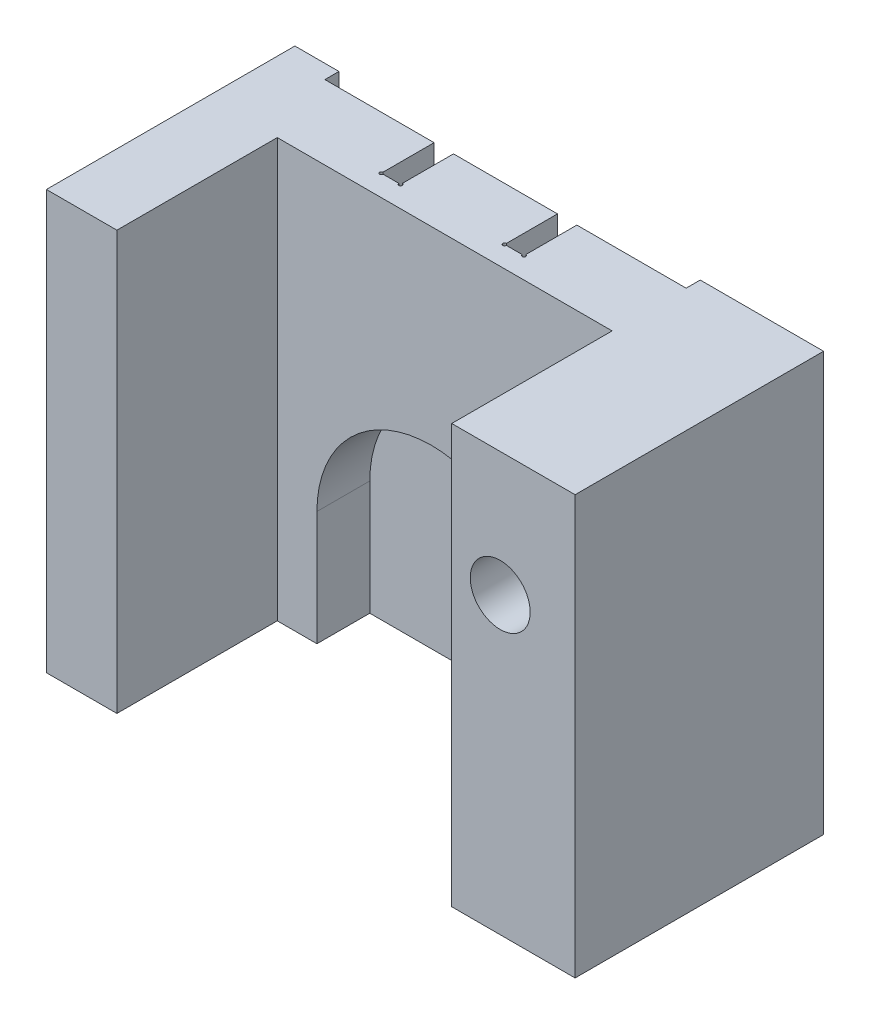
SolidWorks part; units mm, degrees
ref_plane "前视基准面" through (0, 0, 0) normal (0, 0, 1) x (1, 0, 0)
ref_plane "上视基准面" through (0, 0, 0) normal (0, 1, 0) x (1, 0, 0)
ref_plane "右视基准面" through (0, 0, 0) normal (1, 0, 0) x (0, 0, -1)
sketch "草图1" plane through (0, 0, 0) normal (0, 0, 1) x (1, 0, 0)
  line L1 (-7.5503, 16.7364) -> (22.4497, 16.7364)
  line L2 (-7.5503, 16.7364) -> (-7.5503, -11.2636)
  line L3 (-7.5503, -11.2636) -> (22.4497, -11.2636)
  line L4 (22.4497, 16.7364) -> (22.4497, -11.2636)
  dimension "D1" = 30
  dimension "D2" = 28
extrude "凸台-拉伸1" add sketch "草图1" along normal blind 10
sketch "草图2" plane through (0, 0, 0) normal (0, 0, -1) x (-1, 0, 0)
  line L0 (-22.4497, 16.7364) -> (7.5503, 16.7364) construction
  line L1 (7.5503, 16.7364) -> (7.5503, -11.2636) construction
  line L3 (5.0503, 16.7364) -> (-15.4497, 16.7364)
  line L4 (5.0503, 16.7364) -> (5.0503, 3.7364)
  line L5 (2.0503, 0.7364) -> (-12.4497, 0.7364)
  line L6 (-15.4497, 16.7364) -> (-15.4497, 3.7364)
  arc A0 (2.0503, 0.7364) -> (5.0503, 3.7364) centre (2.0503, 3.7364) ccw
  arc A1 (-12.4497, 0.7364) -> (-15.4497, 3.7364) centre (-12.4497, 3.7364) cw
  point P0 (5.0503, 16.7364)
  point P11 (5.0503, 0.7364)
  dimension "D4" = 3
  dimension "D1" = 2.5
  dimension "D2" = 20.5
  dimension "D3" = 16
extrude "切除-拉伸2" cut sketch "草图2" against normal blind 0.8
sketch "草图3" plane through (0, 0, 0.8) normal (0, 0, -1) x (-1, 0, 0)
  line L0 (5.0503, 16.7364) -> (-15.4497, 16.7364) construction
  line L2 (-15.1997, 16.7364) -> (4.8003, 16.7364)
  line L3 (-15.1997, 16.7364) -> (-15.1997, 3.7364)
  line L4 (-12.1997, 0.7364) -> (1.8003, 0.7364)
  line L5 (4.8003, 16.7364) -> (4.8003, 3.7364)
  arc A0 (1.8003, 0.7364) -> (4.8003, 3.7364) centre (1.8003, 3.7364) ccw
  arc A1 (-12.1997, 0.7364) -> (-15.1997, 3.7364) centre (-12.1997, 3.7364) cw
  point P0 (-5.1997, 16.7364)
  point P9 (4.8003, 0.7364)
  point P12 (1.8003, 13.7364)
  point P14 (-12.1997, 13.7364)
  dimension "D4" = 3
  dimension "D1" = 20
  dimension "D2" = 10
  dimension "D3" = 16
  dimension "D5" = 3
  dimension "D6" = 3
  dimension "D7" = 3
  dimension "D8" = 3
hole_wizard "M1.4x0.3 螺纹孔2" positions "草图9" profile "草图7" tap size "M1.4x0.3" standard "ANSI Metric"
sketch "草图9" plane through (0, 0, 0.8) normal (0, 0, -1) x (-1, 0, 0)
  line L1 (-15.1997, 16.7364) -> (4.8003, 16.7364) construction
  point P0 (-12.1997, 8.7364)
  point P3 (1.8003, 8.7364)
  dimension "D1" = 8
  dimension "D2" = 8
sketch "草图7" plane through (12.1997, 8.7364, 0.8) normal (1, 0, 0) x (0, 1, 0)
  line L0 (0, 0) -> (0, 4.0305)
  line L1 (0, 4.0305) -> (0.55, 3.7)
  line L2 (0.55, 3.7) -> (0.55, 0)
  line L5 (0.55, 0) -> (0, 0)
  line L10 (0, 4.0305) -> (-0.55, 3.7) construction
  line L11 (0, -6.35) -> (0, 107.95) construction
  dimension "螺纹孔钻头直径" = 1.1
  dimension "螺纹孔钻头深度" = 3.7
  dimension "导头角度" = 118
cosmetic thread "孔螺蚊线7" parameters "D1"=3.5, "D2"=1.4
cosmetic thread "孔螺蚊线8" parameters "D1"=3.5, "D2"=1.4
sketch "草图10" plane through (0, 16.7364, 0) normal (0, 1, 0) x (1, 0, 0)
  line L0 (22.4497, -0.8) -> (-7.5503, -0.8)
  line L1 (22.4497, -10) -> (22.4497, 0) construction
  line L2 (-7.5503, -10) -> (-7.5503, 0) construction
  line L3 (22.4497, 0) -> (15.4497, 0) construction
  line L5 (9.2497, -0.8) -> (8.1497, -0.8)
  line L6 (9.2497, -0.8) -> (9.2497, -3.7)
  line L7 (9.1495, -3.8) -> (8.2497, -3.8)
  line L8 (8.1497, -0.8) -> (8.1497, -3.7)
  line L9 (1.1497, -0.8) -> (2.2497, -0.8)
  line L10 (1.1497, -0.8) -> (1.1497, -3.7043)
  line L11 (1.2454, -3.8) -> (2.1461, -3.8)
  line L12 (2.2497, -0.8) -> (2.2497, -3.6964)
  arc A0 (9.1495, -3.8) -> (9.2497, -3.7) centre (9.2495, -3.8) ccw
  arc A1 (8.1497, -3.7) -> (8.2497, -3.8) centre (8.1497, -3.8) ccw
  arc A2 (2.1461, -3.8) -> (2.2497, -3.6964) centre (2.2497, -3.8) ccw
  arc A3 (1.1497, -3.7043) -> (1.2454, -3.8) centre (1.1497, -3.8) ccw
  point P8 (5.1997, -0.8)
  point P9 (9.2497, -0.8)
  point P10 (1.1497, -0.8)
  dimension "D9" = 0.1
  dimension "D10" = 0.1
  dimension "D1" = 0.8
  dimension "D2" = 4.05
  dimension "D3" = 4.05
  dimension "D4" = 3
  dimension "D5" = 1.1
  dimension "D6" = 1.1
  dimension "D7" = 3
  dimension "D8" = 12.75
extrude "切除-拉伸3" cut sketch "草图10" against normal blind 4 contours L8 A1 L7 A0 L6 L5 | L10 A3 L11 A2 L12 L9
sketch "草图11" plane through (0, 0, 0) normal (0, 0, -1) x (-1, 0, 0)
  line L0 (-12.1997, 0.7364) -> (1.8003, 0.7364) construction
  line L1 (-7.5497, -2.0636) -> (-2.8497, -2.0636)
  line L2 (-7.7997, 0.7364) -> (-2.5997, 0.7364)
  line L3 (-7.7997, 0.7364) -> (-7.7997, -1.8136)
  line L5 (-2.5997, 0.7364) -> (-2.5997, -1.8136)
  arc A0 (-2.8497, -2.0636) -> (-2.5997, -1.8136) centre (-2.5997, -2.0636) ccw
  arc A1 (-7.7997, -1.8136) -> (-7.5497, -2.0636) centre (-7.7997, -2.0636) ccw
  point P0 (-5.1997, 0.7364)
  dimension "D4" = 2.8
  dimension "D5" = 0.5
  dimension "D6" = 0.5
  dimension "D1" = 5.2
  dimension "D2" = 2.6
  dimension "D3" = 2.8
  dimension "D7" = 2.8
  dimension "D8" = 2.8
  dimension "D9" = 4.7
extrude "切除-拉伸4" cut sketch "草图11" against normal blind 0.5
sketch "草图12" plane through (0, 0, 0) normal (0, 0, -1) x (-1, 0, 0)
  line L0 (-22.4497, -11.2636) -> (-22.4497, 16.7364) construction
  line L1 (7.5503, -11.2636) -> (-22.4497, -11.2636)
  line L2 (7.5503, -11.2636) -> (7.5503, -7.0136)
  line L3 (7.5503, -7.0136) -> (-22.4497, -7.0136)
  line L4 (-22.4497, -11.2636) -> (-22.4497, -7.0136)
  dimension "D1" = 4.25
extrude "切除-拉伸5" cut sketch "草图12" against normal blind 10
sketch "草图13" plane through (0, 0, 0) normal (0, 0, -1) x (-1, 0, 0)
  line L1 (-7.5497, -2.0636) -> (-2.8497, -2.0636) construction
  line L3 (-7.5497, -2.0636) -> (-2.8497, -2.0636) construction
  circle A0 centre (-18.1997, 9.6864) radius 1.7
  point P0 (-18.1997, 9.6864)
  point P6 (-5.1997, -2.0636)
  dimension "D3" = 3.4
  dimension "D1" = 13
  dimension "D2" = 11.75
extrude "切除-拉伸6" cut sketch "草图13" against normal blind 10
sketch "草图14" plane through (0, 0, 10) normal (0, 0, 1) x (1, 0, 0)
  line L0 (-7.5503, -7.0136) -> (22.4497, -7.0136) construction
  line L1 (-7.5503, 16.7364) -> (15.4497, 16.7364)
  line L2 (-7.5503, 16.7364) -> (-7.5503, -7.0136)
  line L3 (-7.5503, -7.0136) -> (15.4497, -7.0136)
  line L4 (15.4497, 16.7364) -> (15.4497, -7.0136)
  line L5 (22.4497, -7.0136) -> (22.4497, 16.7364) construction
  dimension "D1" = 7
extrude "切除-拉伸7" cut sketch "草图14" against normal blind 5
sketch "草图16" plane through (0, 0, 5) normal (0, 0, 1) x (1, 0, 0)
  line L2 (-7.5503, -7.0136) -> (15.4497, -7.0136) construction
  line L3 (-7.5503, 16.7364) -> (-7.5503, -7.0136) construction
  line L5 (-1.3003, -7.0136) -> (11.6997, -7.0136)
  line L7 (-1.3003, -7.0136) -> (-1.3003, -0.5136)
  line L9 (11.6997, -7.0136) -> (11.6997, -0.5136)
  arc A0 (11.6997, -0.5136) -> (-1.3003, -0.5136) centre (5.1997, -0.5136) ccw
  point P0 (5.1997, -7.0136)
  dimension "D4" = 6.5
  dimension "D5" = 6.5
  dimension "D1" = 12.75
  dimension "D2" = 13
  dimension "D3" = 6.5
sketch "草图17" plane through (0, 0, 0.5) normal (0, 0, -1) x (-1, 0, 0)
  line L0 (-2.5997, 0.7364) -> (-7.7997, 0.7364) construction
  line L3 (1.3003, -7.0136) -> (-11.6997, -7.0136) construction
  point P0 (-5.1997, 0.7364)
  point P1 (-5.1997, -0.5136)
  dimension "D1" = 6.5
extrude "切除-拉伸9" cut sketch "草图16" against normal blind 3
sketch "草图20" plane through (0, 0, 10) normal (0, 0, 1) x (1, 0, 0)
  line L1 (15.4497, 16.7364) -> (22.4497, 16.7364)
  line L2 (15.4497, 16.7364) -> (15.4497, -7.0136)
  line L3 (15.4497, -7.0136) -> (22.4497, -7.0136)
  line L4 (22.4497, 16.7364) -> (22.4497, -7.0136)
  circle A0 centre (18.1997, 9.6864) radius 1.7
  dimension "D1" = 3.4
extrude "凸台-拉伸3" add sketch "草图20" along normal blind 4.1
sketch "草图21" plane through (0, 0, 0.8) normal (0, 0, -1) x (-1, 0, 0)
  point P0 (-5.1997, 16.7364)
sketch "草图22" plane through (0, 16.7364, 0) normal (0, 1, 0) x (1, 0, 0)
  line L0 (5.1997, -0.8) -> (5.1997, -5)
  line L1 (15.4497, -5) -> (-7.5503, -5) construction
sketch "草图23" plane through (0, 0, 5) normal (0, 0, 1) x (1, 0, 0)
  line L0 (-7.5503, -7.0136) -> (-1.3003, -7.0136) construction
  line L1 (-7.5503, 16.7364) -> (-3.5503, 16.7364)
  line L2 (-7.5503, 16.7364) -> (-7.5503, -7.0136)
  line L3 (-7.5503, -7.0136) -> (-3.5503, -7.0136)
  line L4 (-3.5503, 16.7364) -> (-3.5503, -7.0136)
  dimension "D1" = 4
extrude "凸台-拉伸4" add sketch "草图23" along normal blind 9.1
